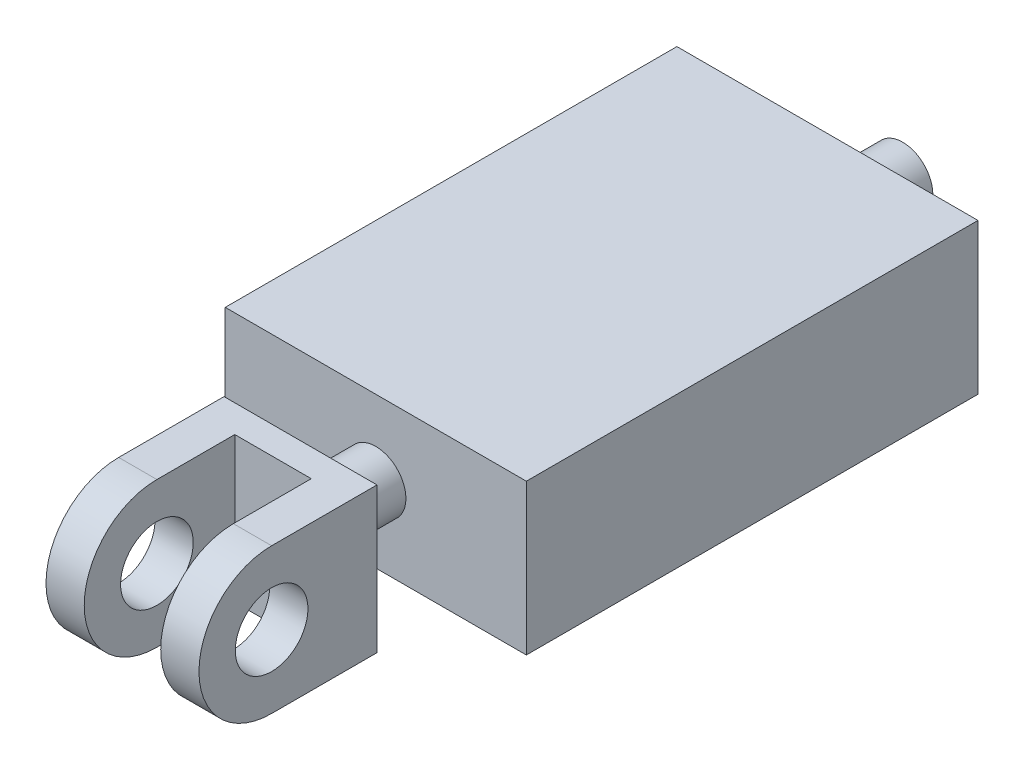
SolidWorks part; units mm, degrees
ref_plane "Front Plane" through (0, 0, 0) normal (0, 0, 1) x (1, 0, 0)
ref_plane "Top Plane" through (0, 0, 0) normal (0, 1, 0) x (1, 0, 0)
ref_plane "Right Plane" through (0, 0, 0) normal (1, 0, 0) x (0, 0, -1)
sketch "Sketch1" plane through (0, 0, 0) normal (0, 1, 0) x (1, 0, 0)
  line L0 (-10, 15) -> (10, -15) construction
  line L1 (-10, -15) -> (10, -15)
  line L2 (-10, -15) -> (-10, 15)
  line L3 (-10, 15) -> (10, 15)
  line L4 (10, -15) -> (10, 15)
  line L5 (-10, -15) -> (0, 0) construction
  line L6 (0, 0) -> (10, 15) construction
  point P5 (0, 0)
  dimension "D1" = 20
  dimension "D2" = 30
extrude "Boss-Extrude1" add sketch "Sketch1" along normal blind 10
sketch "Sketch2" plane through (0, 0, 0) normal (0, 0, 1) x (1, 0, 0)
  line L0 (-8, 9) -> (44368.0157, -22179.0078) construction
  line L1 (0, 0) -> (0, 5) construction
  circle A0 centre (0, 5) radius 2
  dimension "D1" = 4
extrude "Boss-Extrude2" add sketch "Sketch2" along normal blind 20 and the other way blind 20
sketch "Sketch4" plane through (0, 0, 0) normal (1, 0, 0) x (0, 0, -1)
  line L0 (-27, 9.826) -> (-20, 9.826)
  line L1 (-20, 9.826) -> (-20, 0.174)
  line L2 (-20, 0.174) -> (-27, 0.174)
  line L5 (-15, 5) -> (-27, 5) construction
  line L6 (-15, 7) -> (-15, 3) construction
  line L7 (-20, 7) -> (-20, 3) construction
  arc A0 (-27, 9.826) -> (-27, 0.174) centre (-27, 5) ccw
  circle A1 centre (-27, 5) radius 2.413
  point P1 (0, 0)
  point P5 (-10, 5)
  dimension "D1" = 4.826
  dimension "D3" = 4.826
  dimension "D2" = 7
extrude "Boss-Extrude3" add sketch "Sketch4" along normal blind 5.08 and the other way blind 5.08
sketch "Sketch5" plane through (0, 9.826, 0) normal (0, 1, 0) x (1, 0, 0)
  line L3 (-5.08, -31.826) -> (5.08, -31.826) construction
  line L14 (-2.54, -21.826) -> (-2.54, -31.826)
  line L15 (-2.54, -31.826) -> (2.54, -31.826)
  line L16 (2.54, -31.826) -> (2.54, -21.826)
  line L18 (-2.54, -21.826) -> (-5.08, -21.826) construction
  line L19 (-5.08, -20) -> (-5.08, -27) construction
  line L20 (-2.54, -21.826) -> (2.54, -21.826)
  line L21 (2.54, -21.826) -> (5.08, -21.826) construction
  line L22 (5.08, -20) -> (5.08, -27) construction
  dimension "D1" = 10
  dimension "D3" = 5.08
extrude "Cut-Extrude1" cut sketch "Sketch5" against normal through all
